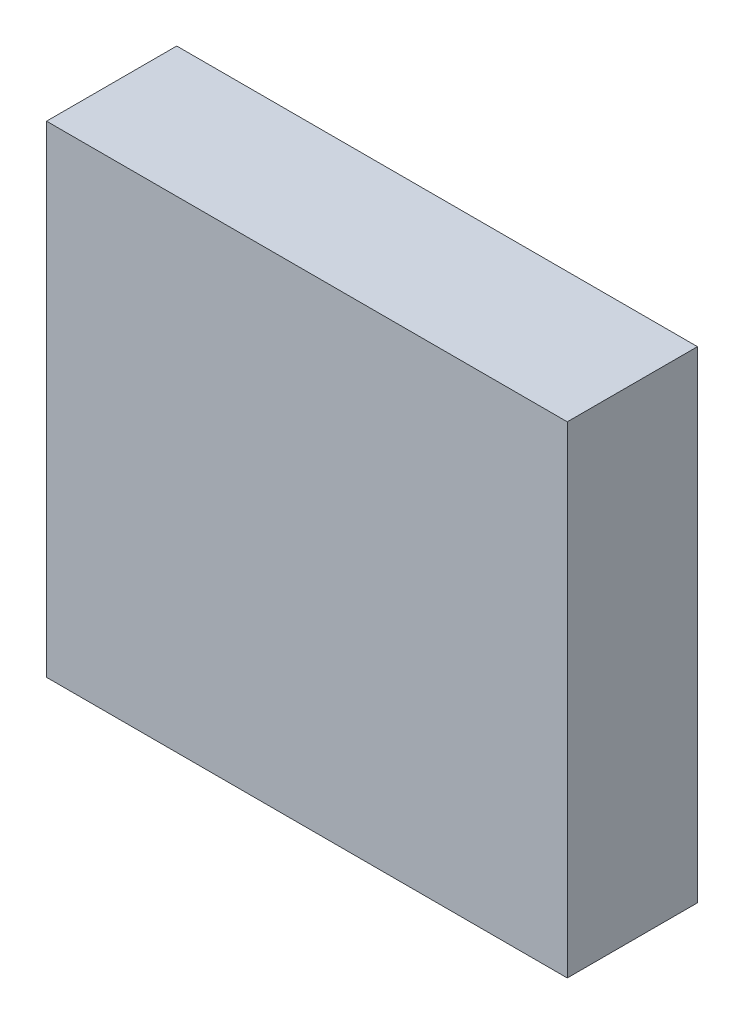
SolidWorks part; units mm, degrees
ref_plane "Front Plane" through (0, 0, 0) normal (0, 0, 1) x (1, 0, 0)
ref_plane "Top Plane" through (0, 0, 0) normal (0, 1, 0) x (1, 0, 0)
ref_plane "Right Plane" through (0, 0, 0) normal (1, 0, 0) x (0, 0, -1)
sketch "Sketch1" plane through (0, 0, 0) normal (0, 0, 1) x (1, 0, 0)
  line L1 (0, 0) -> (40, 0)
  line L2 (0, 0) -> (0, 37)
  line L3 (0, 37) -> (40, 37)
  line L4 (40, 0) -> (40, 37)
extrude "Boss-Extrude1" add sketch "Sketch1" against normal blind 10
